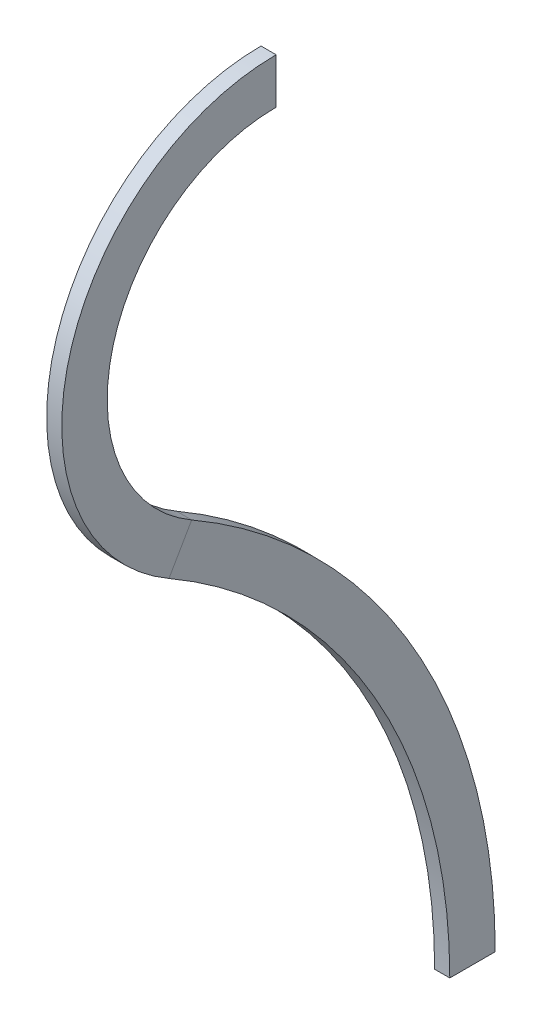
SolidWorks part; units mm, degrees
material "Thornel Mat VMA"
ref_plane "Front Plane" through (0, 0, 0) normal (0, 0, 1) x (1, 0, 0)
ref_plane "Top Plane" through (0, 0, 0) normal (0, 1, 0) x (1, 0, 0)
ref_plane "Right Plane" through (0, 0, 0) normal (1, 0, 0) x (0, 0, -1)
sketch "Sketch1" plane through (0, 0, 0) normal (1, 0, 0) x (0, 0, -1)
  line L0 (0, 140) -> (0, 0) construction
  line L1 (0, 140) -> (45.8684, 140) construction
  line L2 (0, 0) -> (23, 0) construction
  arc A0 (0, 140) -> (-25.6218, 44.3782) centre (0, 88.7564) ccw construction
  arc A1 (-25.6218, 44.3782) -> (0, 0) centre (-51.2436, 0) cw construction
  arc A2 (0, 117) -> (-14.1218, 64.2968) centre (0, 88.7564) ccw
  arc A3 (-14.1218, 64.2968) -> (23, 0) centre (-51.2436, 0) cw
  dimension "D2" = 23
  dimension "D3" = 23
  dimension "D1" = 140
sketch "Sketch2" plane through (0, 0, 0) normal (0, 1, 0) x (1, 0, 0)
  line L0 (0, 0) -> (0, 45.8684) construction
  line L1 (0, 22.9342) -> (2, 22.9342)
  line L2 (0, 22.9342) -> (0, 28.9342)
  line L3 (0, 28.9342) -> (2, 28.9342)
  line L4 (2, 22.9342) -> (2, 28.9342)
  dimension "D1" = 2
  dimension "D2" = 6
sweep "Sweep1" add profiles "Sketch2" path "Sketch1"
